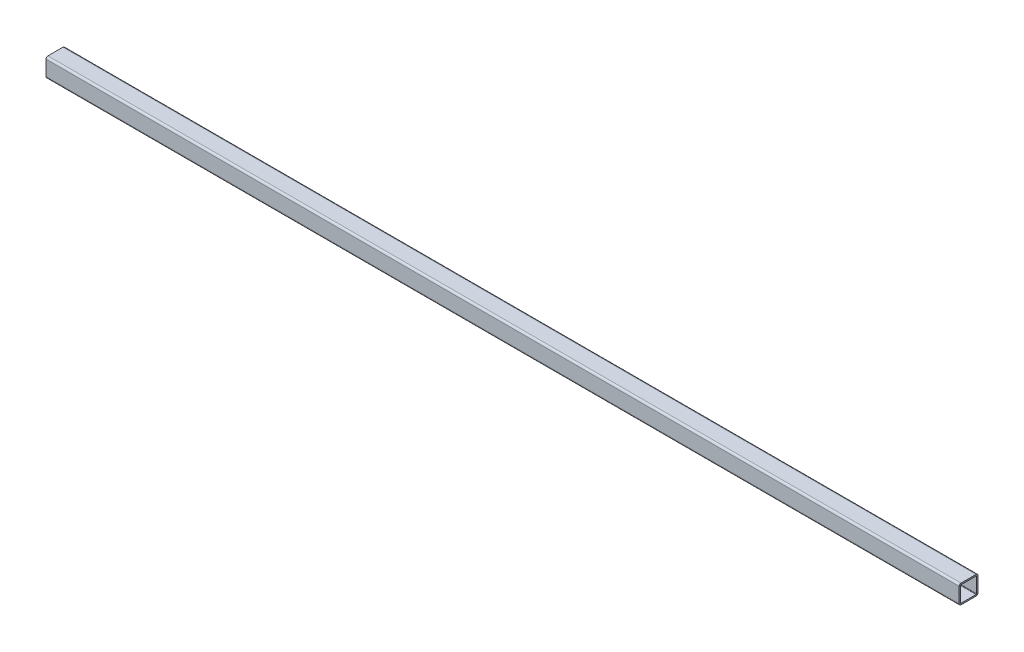
SolidWorks part; units mm, degrees
ref_plane "Спереди" through (0, 0, 0) normal (0, 0, 1) x (1, 0, 0)
ref_plane "Сверху" through (0, 0, 0) normal (0, 1, 0) x (1, 0, 0)
ref_plane "Справа" through (0, 0, 0) normal (1, 0, 0) x (0, 0, -1)
sketch "Эскиз1" plane through (0, 0, 0) normal (0, 0, 1) x (1, 0, 0)
  line L0 (-484.5, 0) -> (484.5, 0)
  dimension "D1" = 969
other "Квадратная труба 2 X 2 X 0.25(1)"
ref_plane "Плоскость1" through (-484.5, 0, 0) normal (1, 0, 0) x (0, 1, 0)
sketch "Sketch1" plane through (-484.5, 0, 0) normal (1, 0, 0) x (0, 1, 0)
  line L0 (-8, -8.5) -> (8, -8.5)
  line L1 (-8.5, -8) -> (-8.5, 8)
  line L2 (8, 8.5) -> (-8, 8.5)
  line L3 (8.5, 8) -> (8.5, -8)
  line L4 (-8, -10) -> (8, -10)
  line L5 (-10, -8) -> (-10, 8)
  line L6 (8, 10) -> (-8, 10)
  line L7 (10, 8) -> (10, -8)
  line L8 (0, 0) -> (8.5, 0) construction
  line L9 (0, 0) -> (0, 8.5) construction
  arc A0 (10, 8) -> (8, 10) centre (8, 8) ccw
  arc A1 (8, -10) -> (10, -8) centre (8, -8) ccw
  arc A2 (-10, -8) -> (-8, -10) centre (-8, -8) ccw
  arc A3 (-8, 10) -> (-10, 8) centre (-8, 8) ccw
  arc A4 (-8, 8.5) -> (-8.5, 8) centre (-8, 8) ccw
  arc A5 (8.5, 8) -> (8, 8.5) centre (8, 8) ccw
  arc A6 (8, -8.5) -> (8.5, -8) centre (8, -8) ccw
  arc A7 (-8.5, -8) -> (-8, -8.5) centre (-8, -8) ccw
  point P3 (0, 10)
  point P4 (10, 0)
  point P5 (0, -10)
  point P6 (-10, 0)
  point P7 (-10, 10)
  point P8 (-10, -10)
  point P33 (0, 0)
  point P35 (10, -10)
  point P36 (10, 10)
  point P37 (0, 0)
  dimension "D1" = 2
  dimension "1,5" = 1.5
  dimension "V_leg" = 20
